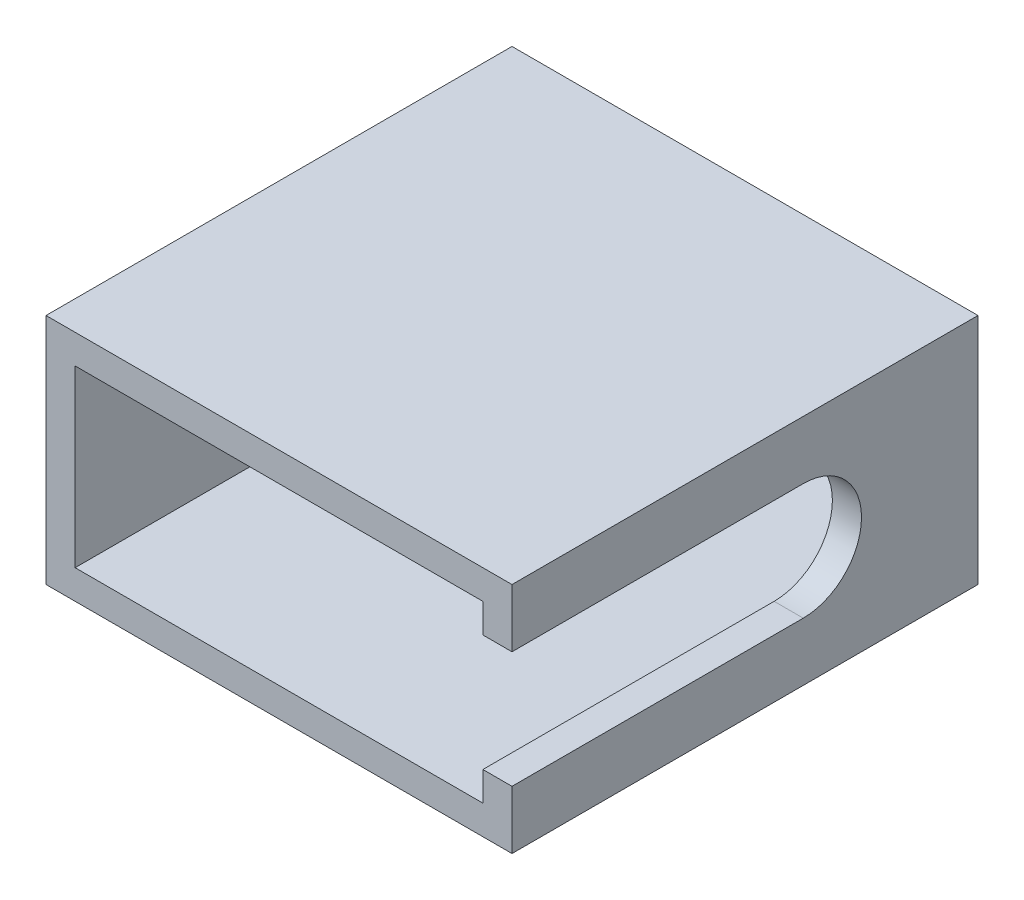
SolidWorks part; units mm, degrees
ref_plane "Front Plane" through (0, 0, 0) normal (0, 0, 1) x (1, 0, 0)
ref_plane "Top Plane" through (0, 0, 0) normal (0, 1, 0) x (1, 0, 0)
ref_plane "Right Plane" through (0, 0, 0) normal (1, 0, 0) x (0, 0, -1)
sketch "Sketch1" plane through (0, 0, 0) normal (0, 0, 1) x (1, 0, 0)
  line L1 (-25.4, 12.7) -> (25.4, 12.7)
  line L2 (-25.4, 12.7) -> (-25.4, -12.7)
  line L3 (-25.4, -12.7) -> (25.4, -12.7)
  line L4 (25.4, 12.7) -> (25.4, -12.7)
  line L5 (-25.4, 12.7) -> (25.4, -12.7) construction
  line L6 (-25.4, -12.7) -> (25.4, 12.7) construction
  point P0 (0, 0)
  dimension "D1" = 50.8
  dimension "D2" = 25.4
extrude "Boss-Extrude1" add sketch "Sketch1" along normal blind 50.8
shell "Shell1" thickness 3.175
sketch "Sketch2" plane through (25.4, 0, 0) normal (1, 0, 0) x (0, 0, -1)
  line L0 (-50.8, -12.7) -> (-50.8, 12.7) construction
  line L1 (-50.8, -6.35) -> (-19.05, -6.35)
  line L2 (-50.8, -6.35) -> (-50.8, 6.35)
  line L3 (-50.8, 6.35) -> (-19.05, 6.35)
  arc A0 (-19.05, -6.35) -> (-19.05, 6.35) centre (-19.05, 0) ccw
  dimension "D1" = 31.75
  dimension "D2" = 6.35
  dimension "D3" = 12.7
extrude "Cut-Extrude1" cut sketch "Sketch2" against normal up to next
